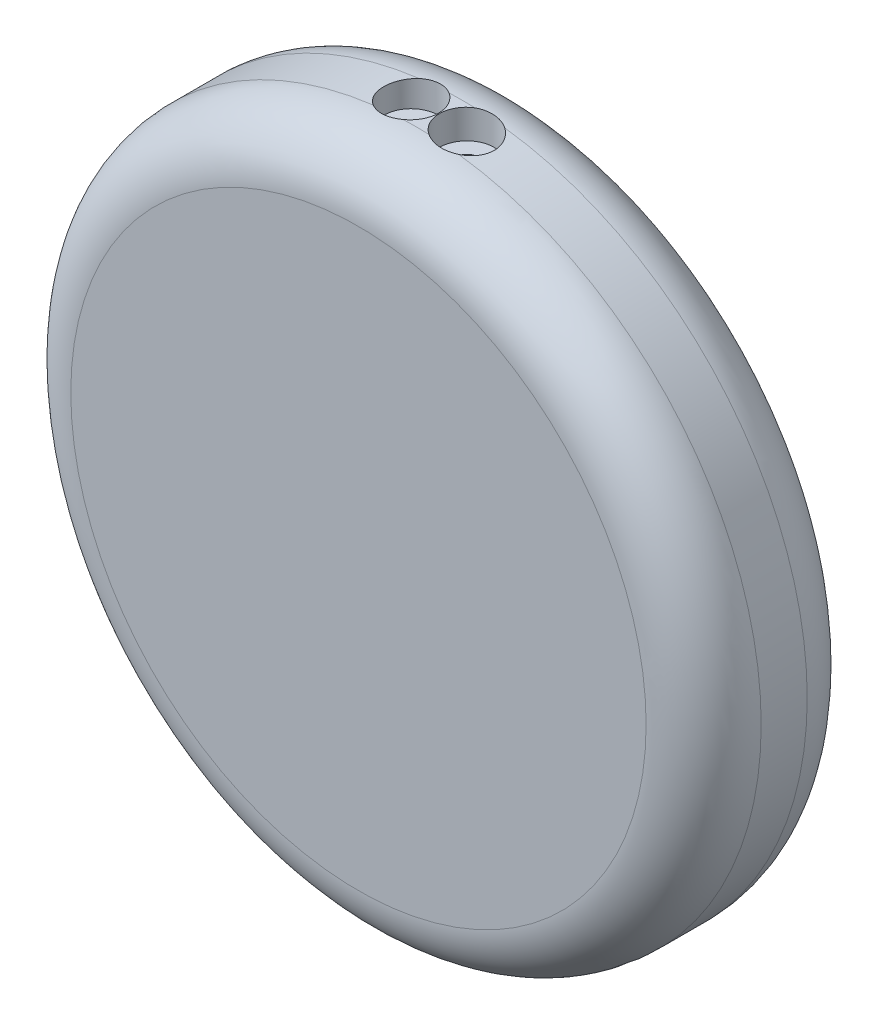
SolidWorks part; units mm, degrees
ref_plane "Front Plane" through (0, 0, 0) normal (0, 0, 1) x (1, 0, 0)
ref_plane "Top Plane" through (0, 0, 0) normal (0, 1, 0) x (1, 0, 0)
ref_plane "Right Plane" through (0, 0, 0) normal (1, 0, 0) x (0, 0, -1)
sketch "Sketch1" plane through (0, 0, 0) normal (0, 0, 1) x (1, 0, 0)
  circle A0 centre (0, 0) radius 75
  dimension "D1" = 150
extrude "Boss-Extrude1" add sketch "Sketch1" along normal blind 35
sketch "Sketch2" plane through (0, 0, 0) normal (0, 1, 0) x (1, 0, 0)
  line L0 (-75, 0) -> (75, 0) construction
  line L1 (75, 0) -> (75, -35) construction
  line L2 (75, -35) -> (-75, -35) construction
  line L3 (-75, -35) -> (-75, 0) construction
  line L4 (-6.045, -17.5) -> (6.045, -17.5) construction
  circle A0 centre (-6.045, -17.5) radius 2.3813
  circle A1 centre (6.045, -17.5) radius 2.3813
  point P12 (75, -17.5)
  point P13 (0, -17.5)
  dimension "D2" = 4.7625
  dimension "D3" = 4.7625
  dimension "D1" = 12.09
extrude "Cut-Extrude1" cut sketch "Sketch2" against normal through all both and the other way through all
fillet "Fillet1" radius 12.5 2 edges at (75, 0, 35) (75, 0, 0)
ref_plane "Plane1" through (0, 75, 0) normal (0, 1, 0) x (1, 0, 0)
sketch "Sketch3" plane through (0, 75, 0) normal (0, 1, 0) x (1, 0, 0)
  circle A0 centre (-6.045, -17.5) radius 5.9531
  circle A1 centre (6.045, -17.5) radius 5.9531
  dimension "D1" = 11.9062
  dimension "D2" = 11.9062
extrude "Cut-Extrude2" cut sketch "Sketch3" against normal blind 6.35
